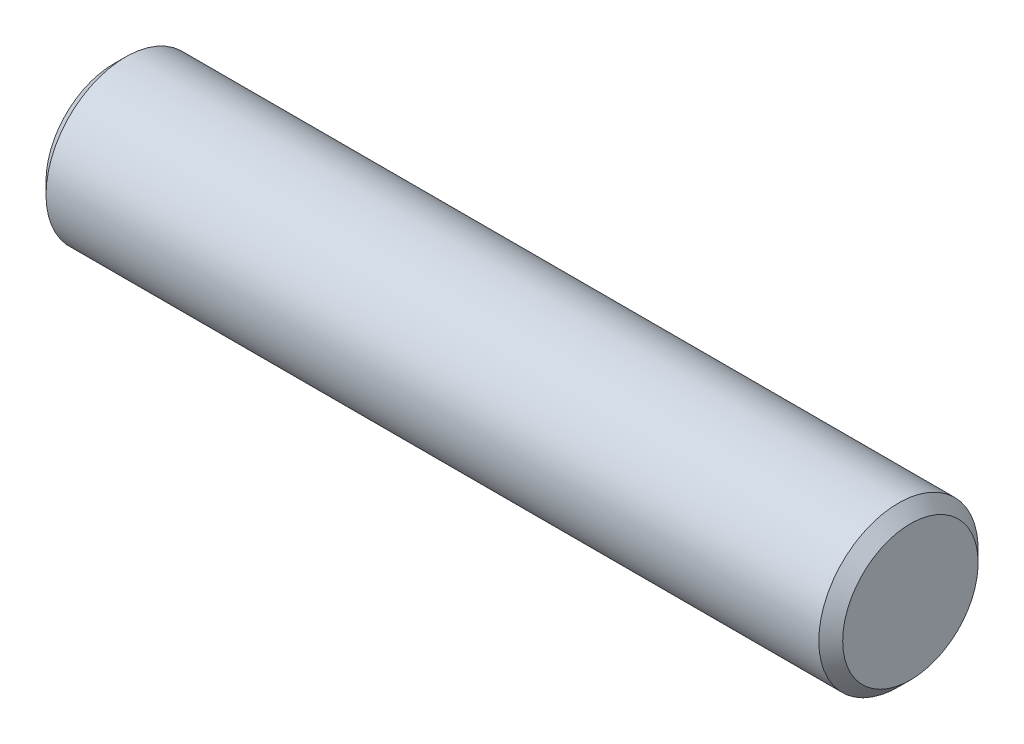
SolidWorks part; units mm, degrees
ref_plane "Plane1" through (0, 0, 0) normal (0, 0, 1) x (1, 0, 0)
ref_plane "Plane2" through (0, 0, 0) normal (0, 1, 0) x (1, 0, 0)
ref_plane "Plane3" through (0, 0, 0) normal (1, 0, 0) x (0, 0, -1)
sketch "BodySke" plane through (0, 0, 0) normal (0, 0, 1) x (1, 0, 0)
  line L0 (3, 19.05) -> (3, -3.175) construction
  line L5 (1.5, 10) -> (0, 8.5)
  line L10 (1.5, 10) -> (98.5, 10)
  line L11 (98.5, 10) -> (100, 8.5)
  line L12 (100, 8.5) -> (100, 0)
  line L13 (100, 0) -> (0, 0)
  line L14 (-3.175, 0) -> (101.6, 0) construction
  line L15 (86.0126, -8.5) -> (100, -8.5) construction
  line L17 (-8.966, -10.0001) -> (54, -10.0001) construction
  line L18 (0, 8.5) -> (0, 0)
  dimension "Minor_dia" = 17
  dimension "Thread_ch_ang" = 45
  dimension "Thread_dia" = 20
  dimension "Length" = 100
  dimension "Body_ch_ang" = 45
  dimension "Advance" = 3
revolve "BaseBody" add sketch "BodySke" angle 360 about L14
cosmetic thread "ThreadCosmetic" [suppressed] parameters "Thread_minor"=17
sketch "ThdSchSke" plane through (0, 0, 0) normal (0, 0, 1) x (1, 0, 0)
  line L0 (98.5, -8.5) -> (97.4497, -10)
  line L1 (98.5, -8.5) -> (99.5503, -10)
  line L2 (99.5503, -10) -> (99.5503, -12.5)
  line L3 (-3.175, 0) -> (5.1513, 0) construction
  line L4 (98.5, 10) -> (98.5, -10) construction
  line L5 (99.5503, -12.5) -> (97.4497, -12.5)
  line L6 (97.4497, -12.5) -> (97.4497, -10)
  dimension "Thread_minor" = 17
  dimension "SideAngle" = 55
  dimension "VeeAngle" = 70
  dimension "Overcut" = 25
  dimension "Diameter" = 20
revolve "ThreadSchematic" [suppressed] cut sketch "ThdSchSke" angle 360 about L3
pattern_linear "ThdSchPat" [suppressed]
equation "\"Thread_minor@ThreadCosmetic\" = \"Minor_dia@BodySke\""
equation "\"Thread_minor@ThdSchSke\" = \"Minor_dia@BodySke\""
equation "\"Diameter@ThdSchSke\" = \"Thread_dia@BodySke\""
equation "\"Overcut@ThdSchSke\" = \"Thread_dia@BodySke\" * 1.25"
equation "\"Num_threads@ThdSchPat\" = int( ( \"Length@BodySke\" - \"Advance@BodySke\" ) / \"Advance@BodySke\" + 0.999 ) + 1"
equation "\"Advance@ThdSchPat\" = \"Length@BodySke\" /  ( \"Num_threads@ThdSchPat\" - 1 ) 'relax it"
equation "\"Num_threads@ThdSchPat\" = \"Num_threads@ThdSchPat\" - sgn( \"Num_threads@ThdSchPat\" - 1 ) '---chamfered tips only---"
